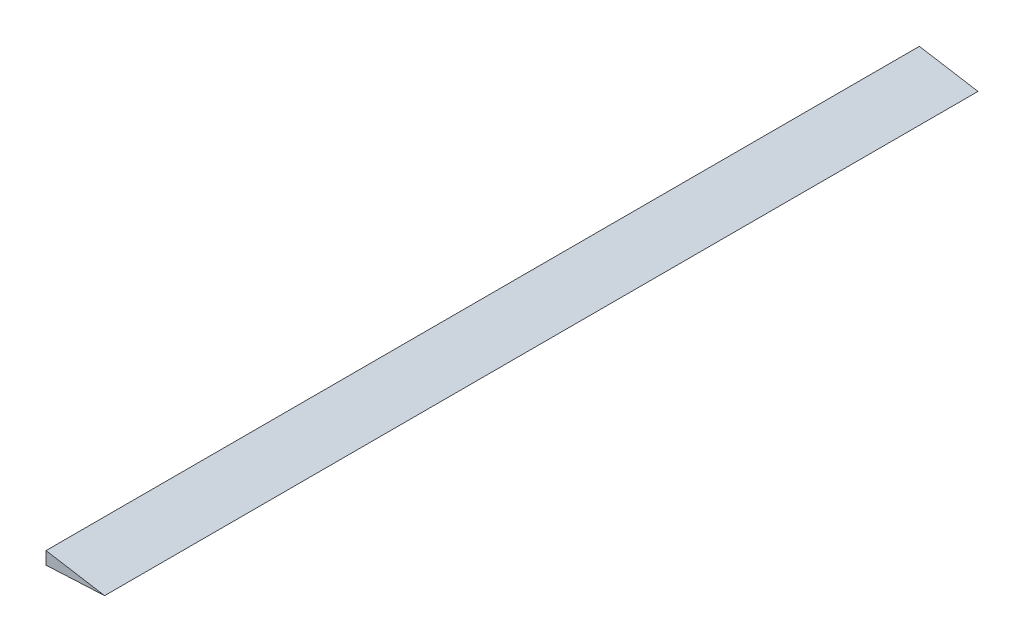
SolidWorks part; units mm, degrees
material "Balsa"
ref_plane "Front Plane" through (0, 0, 0) normal (0, 0, 1) x (1, 0, 0)
ref_plane "Top Plane" through (0, 0, 0) normal (0, 1, 0) x (1, 0, 0)
ref_plane "Right Plane" through (0, 0, 0) normal (1, 0, 0) x (0, 0, -1)
sketch "Sketch1" plane through (0, 0, 0) normal (0, 0, 1) x (1, 0, 0)
  line L0 (306.8496, -2.5161) -> (306.8496, 8.4499) construction
  line L1 (306.8496, -2.5161) -> (306.8496, 8.4499)
  line L2 (306.8496, 8.4499) -> (357.6496, 0)
  line L3 (306.8496, -2.5161) -> (357.6496, 0)
  spline S0 degree 3 poles (354.9573, 0.0431) (358.3317, -0.0432) (354.9981, 0.2938) (352.3707, 0.8024) (346.1763, 1.8676) (338.7813, 3.2655) (329.3081, 4.8919) (318.2482, 6.6648) (305.5952, 8.6507) (291.564, 10.8193) (276.34, 13.1505) (260.1392, 15.5903) (243.1815, 18.0913) (225.699, 20.6027) (207.9209, 23.0318) (190.087, 25.3152) (172.4086, 27.3328) (155.0467, 28.9096) (138.1258, 29.947) (121.7437, 30.3922) (105.9899, 30.2108) (90.9433, 29.4155) (76.6903, 28.0308) (63.3272, 26.1868) (50.9728, 23.9485) (39.7523, 21.3791) (29.7714, 18.545) (21.1318, 15.5018) (13.8914, 12.3237) (8.1391, 9.1075) (3.8158, 5.9031) (1.1802, 2.9693) (-0.4877, -0.018) (1.2572, -2.9285) (4.805, -4.6528) (9.8754, -6.6365) (16.78, -8.2511) (25.3535, -9.7017) (35.5828, -10.8813) (47.3622, -11.8027) (60.5842, -12.4624) (75.1117, -12.8607) (90.7897, -13.0132) (107.4435, -12.9137) (124.9052, -12.5651) (143.0256, -11.8868) (161.6617, -10.9405) (180.6424, -9.8572) (199.7442, -8.7119) (218.721, -7.5525) (237.3263, -6.4253) (255.3201, -5.3536) (272.4652, -4.367) (288.5372, -3.4753) (303.3148, -2.6922) (316.6121, -2.0207) (328.2104, -1.4385) (338.1246, -0.9102) (345.8395, -0.4061) (352.2525, -0.129) (354.9573, 0.0431) (358.3317, -0.0432) (354.9981, 0.2938) knots -0.015092 -0.006889 -0.001754 0 0.001748 0.006827 0.01488 0.025572 0.038694 0.054171 0.071834 0.091435 0.112685 0.135293 0.158944 0.183315 0.20807 0.232879 0.257399 0.281384 0.304706 0.327241 0.348897 0.369607 0.389308 0.407886 0.425177 0.441027 0.4553 0.467904 0.478752 0.487814 0.49509 0.500617 0.504451 0.507804 0.513091 0.520546 0.530249 0.542214 0.556382 0.572656 0.590895 0.610925 0.632536 0.655496 0.679547 0.704499 0.730211 0.756436 0.782837 0.809062 0.834776 0.859641 0.883338 0.905541 0.925965 0.944326 0.960366 0.973929 0.984908 0.993111 0.998246 1 1.001748 1.006827 1.01488 only from (357.6496, 0) to (357.6496, 0) construction
  spline S1 degree 3 poles (354.9573, 0.0431) (358.3317, -0.0432) (354.9981, 0.2938) (352.3707, 0.8024) (346.1763, 1.8676) (338.7813, 3.2655) (329.3081, 4.8919) (318.2482, 6.6648) (305.5952, 8.6507) (291.564, 10.8193) (276.34, 13.1505) (260.1392, 15.5903) (243.1815, 18.0913) (225.699, 20.6027) (207.9209, 23.0318) (190.087, 25.3152) (172.4086, 27.3328) (155.0467, 28.9096) (138.1258, 29.947) (121.7437, 30.3922) (105.9899, 30.2108) (90.9433, 29.4155) (76.6903, 28.0308) (63.3272, 26.1868) (50.9728, 23.9485) (39.7523, 21.3791) (29.7714, 18.545) (21.1318, 15.5018) (13.8914, 12.3237) (8.1391, 9.1075) (3.8158, 5.9031) (1.1802, 2.9693) (-0.4877, -0.018) (1.2572, -2.9285) (4.805, -4.6528) (9.8754, -6.6365) (16.78, -8.2511) (25.3535, -9.7017) (35.5828, -10.8813) (47.3622, -11.8027) (60.5842, -12.4624) (75.1117, -12.8607) (90.7897, -13.0132) (107.4435, -12.9137) (124.9052, -12.5651) (143.0256, -11.8868) (161.6617, -10.9405) (180.6424, -9.8572) (199.7442, -8.7119) (218.721, -7.5525) (237.3263, -6.4253) (255.3201, -5.3536) (272.4652, -4.367) (288.5372, -3.4753) (303.3148, -2.6922) (316.6121, -2.0207) (328.2104, -1.4385) (338.1246, -0.9102) (345.8395, -0.4061) (352.2525, -0.129) (354.9573, 0.0431) (358.3317, -0.0432) (354.9981, 0.2938) knots -0.015092 -0.006889 -0.001754 0 0.001748 0.006827 0.01488 0.025572 0.038694 0.054171 0.071834 0.091435 0.112685 0.135293 0.158944 0.183315 0.20807 0.232879 0.257399 0.281384 0.304706 0.327241 0.348897 0.369607 0.389308 0.407886 0.425177 0.441027 0.4553 0.467904 0.478752 0.487814 0.49509 0.500617 0.504451 0.507804 0.513091 0.520546 0.530249 0.542214 0.556382 0.572656 0.590895 0.610925 0.632536 0.655496 0.679547 0.704499 0.730211 0.756436 0.782837 0.809062 0.834776 0.859641 0.883338 0.905541 0.925965 0.944326 0.960366 0.973929 0.984908 0.993111 0.998246 1 1.001748 1.006827 1.01488 only from (357.6496, 0) to (357.6496, 0)
sketch "Sketch2" plane through (0, 0, -761.9997) normal (0, 0, -1) x (-1, 0, 0)
  line L0 (-306.8496, -2.5161) -> (-306.8496, 8.4499) construction
  line L1 (-306.8496, -2.5161) -> (-357.6496, 0) construction
  line L2 (-306.8496, 8.4499) -> (-357.6496, 0) construction
  line L3 (-306.8496, -2.5161) -> (-306.8496, 8.4499)
  line L4 (-306.8496, -2.5161) -> (-357.6496, 0)
  line L5 (-306.8496, 8.4499) -> (-357.6496, 0)
extrude "Boss-Extrude2" add sketch "Sketch2" against normal up to surface (756.9197 mm away)
